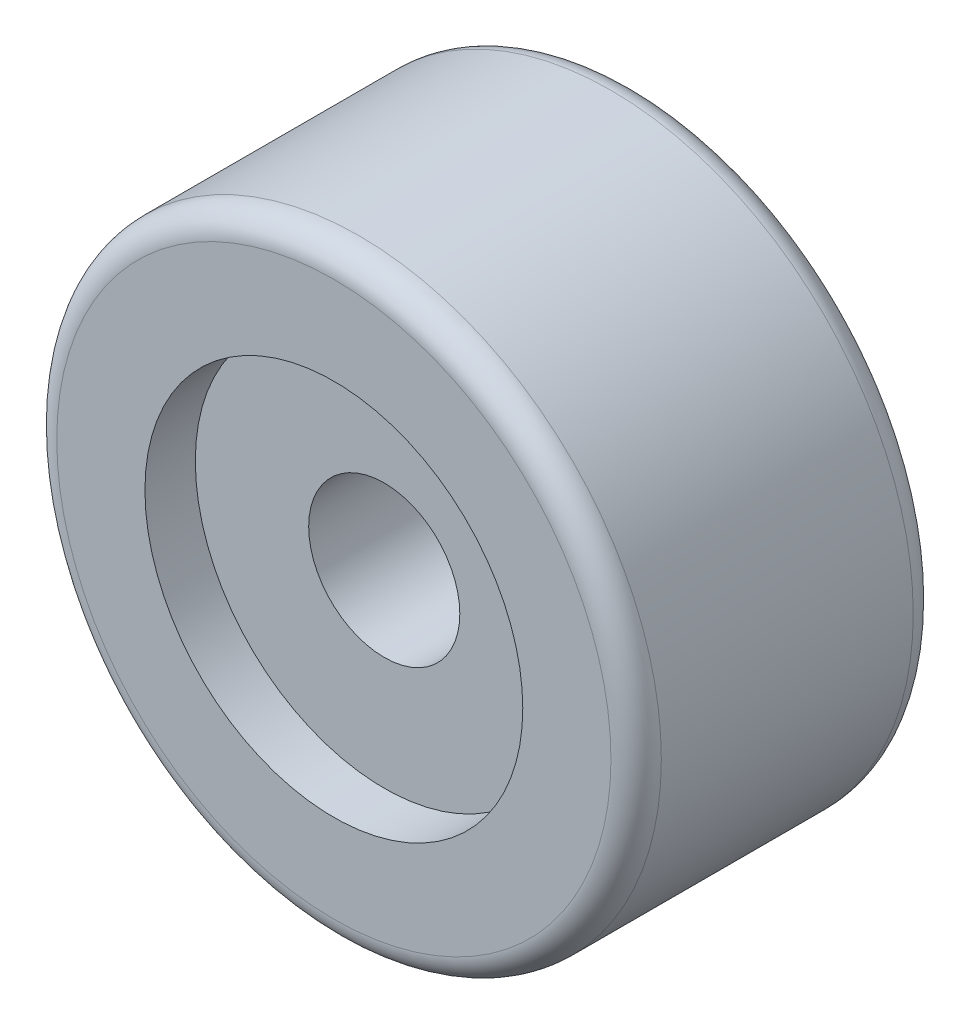
SolidWorks part; units mm, degrees
material "Tough PLA"
ref_plane "前视基准面" through (0, 0, 0) normal (0, 0, 1) x (1, 0, 0)
ref_plane "上视基准面" through (0, 0, 0) normal (0, 1, 0) x (1, 0, 0)
ref_plane "右视基准面" through (0, 0, 0) normal (1, 0, 0) x (0, 0, -1)
sketch "草图1" plane through (0, 0, 0) normal (0, 0, 1) x (1, 0, 0)
  circle A0 centre (0, 0) radius 6
  circle A1 centre (0, 0) radius 1.5
  dimension "D1" = 12
  dimension "D2" = 3
extrude "凸台-拉伸1" add sketch "草图1" along normal blind 6
sketch "草图2" plane through (0, 0, 6) normal (0, 0, 1) x (1, 0, 0)
  circle A0 centre (0, 0) radius 3.75
  dimension "D1" = 7.5
extrude "切除-拉伸1" cut sketch "草图2" against normal blind 1
sketch "草图3" plane through (0, 0, 0) normal (0, 0, -1) x (-1, 0, 0)
  circle A0 centre (0, 0) radius 3.75
  dimension "D1" = 7.5
extrude "切除-拉伸2" cut sketch "草图3" against normal blind 1
fillet "圆角1" radius 0.5 2 edges at (6, 0, 0) (6, 0, 6)
